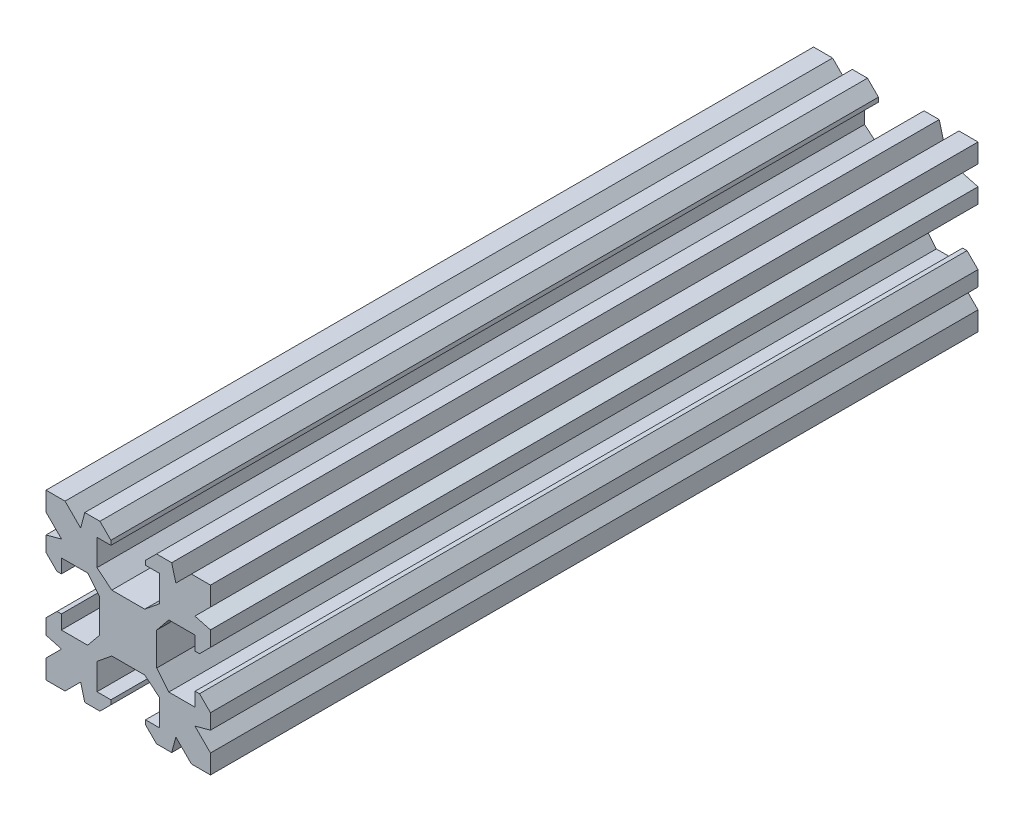
SolidWorks part; units mm, degrees
ref_plane "Спереди" through (0, 0, 0) normal (0, 0, 1) x (1, 0, 0)
ref_plane "Сверху" through (0, 0, 0) normal (0, 1, 0) x (1, 0, 0)
ref_plane "Справа" through (0, 0, 0) normal (1, 0, 0) x (0, 0, -1)
sketch "Эскиз1" plane through (0, 0, 0) normal (0, 0, 1) x (1, 0, 0)
  line L0 (1.58, 6.1) -> (2.85, 6.1)
  line L1 (-7.5, -7.5) -> (7.5, -7.5)
  line L2 (-7.5, -7.5) -> (-7.5, 7.5)
  line L3 (-7.5, 7.5) -> (7.5, 7.5)
  line L4 (7.5, -7.5) -> (7.5, 7.5)
  line L5 (-2.85, 6.1) -> (-1.58, 6.1)
  line L6 (-2.85, 6.1) -> (-2.85, 3.7)
  line L7 (-2.85, 3.7) -> (2.85, 3.7)
  line L8 (2.85, 6.1) -> (2.85, 3.7)
  line L9 (-2.85, 6.1) -> (2.85, 3.7) construction
  line L10 (-2.85, 3.7) -> (2.85, 6.1) construction
  line L11 (-1.58, 7.5) -> (1.58, 7.5)
  line L12 (-1.58, 7.5) -> (-1.58, 6.1)
  line L14 (1.58, 7.5) -> (1.58, 6.1)
  line L15 (-1.58, 7.5) -> (1.58, 6.1) construction
  line L16 (-1.58, 6.1) -> (1.58, 7.5) construction
  line L17 (6.1, -1.58) -> (6.1, -2.85)
  line L18 (6.1, 2.85) -> (6.1, 1.58)
  line L19 (6.1, 2.85) -> (3.7, 2.85)
  line L20 (3.7, 2.85) -> (3.7, -2.85)
  line L21 (6.1, -2.85) -> (3.7, -2.85)
  line L22 (7.5, 1.58) -> (7.5, -1.58)
  line L23 (7.5, 1.58) -> (6.1, 1.58)
  line L24 (7.5, -1.58) -> (6.1, -1.58)
  line L25 (6.1, 2.85) -> (3.7, -2.85) construction
  line L26 (3.7, 2.85) -> (6.1, -2.85) construction
  line L27 (7.5, 1.58) -> (6.1, -1.58) construction
  line L28 (6.1, 1.58) -> (7.5, -1.58) construction
  line L29 (-1.58, -6.1) -> (-2.85, -6.1)
  line L30 (2.85, -6.1) -> (1.58, -6.1)
  line L31 (2.85, -6.1) -> (2.85, -3.7)
  line L32 (2.85, -3.7) -> (-2.85, -3.7)
  line L33 (-2.85, -6.1) -> (-2.85, -3.7)
  line L34 (1.58, -7.5) -> (-1.58, -7.5)
  line L35 (1.58, -7.5) -> (1.58, -6.1)
  line L36 (-1.58, -7.5) -> (-1.58, -6.1)
  line L37 (2.85, -6.1) -> (-2.85, -3.7) construction
  line L38 (2.85, -3.7) -> (-2.85, -6.1) construction
  line L39 (1.58, -7.5) -> (-1.58, -6.1) construction
  line L40 (1.58, -6.1) -> (-1.58, -7.5) construction
  line L41 (-6.1, 1.58) -> (-6.1, 2.85)
  line L42 (-6.1, -2.85) -> (-6.1, -1.58)
  line L43 (-6.1, -2.85) -> (-3.7, -2.85)
  line L44 (-3.7, -2.85) -> (-3.7, 2.85)
  line L45 (-6.1, 2.85) -> (-3.7, 2.85)
  line L46 (-7.5, -1.58) -> (-7.5, 1.58)
  line L47 (-7.5, -1.58) -> (-6.1, -1.58)
  line L48 (-7.5, 1.58) -> (-6.1, 1.58)
  line L49 (-6.1, -2.85) -> (-3.7, 2.85) construction
  line L50 (-3.7, -2.85) -> (-6.1, 2.85) construction
  line L51 (-7.5, -1.58) -> (-6.1, 1.58) construction
  line L52 (-6.1, -1.58) -> (-7.5, 1.58) construction
  line L53 (-5.762, 7.5) -> (-4.342, 6.08)
  line L54 (-4.342, 6.08) -> (-3.962, 7.5)
  line L55 (-3.962, 7.5) -> (-5.762, 7.5)
  line L56 (-7.5, 7.5) -> (0, 0) construction
  line L57 (-6.08, 4.342) -> (-7.5, 3.962)
  line L58 (-7.5, 5.762) -> (-6.08, 4.342)
  line L59 (-7.5, 3.962) -> (-7.5, 5.762)
  line L60 (4.342, 6.08) -> (3.962, 7.5)
  line L61 (3.962, 7.5) -> (5.762, 7.5)
  line L62 (5.762, 7.5) -> (4.342, 6.08)
  line L63 (7.5, 3.962) -> (7.5, 5.762)
  line L64 (7.5, 5.762) -> (6.08, 4.342)
  line L65 (6.08, 4.342) -> (7.5, 3.962)
  line L66 (6.08, -4.342) -> (7.5, -3.962)
  line L67 (7.5, -3.962) -> (7.5, -5.762)
  line L68 (7.5, -5.762) -> (6.08, -4.342)
  line L69 (3.962, -7.5) -> (5.762, -7.5)
  line L70 (5.762, -7.5) -> (4.342, -6.08)
  line L71 (4.342, -6.08) -> (3.962, -7.5)
  line L72 (-4.342, -6.08) -> (-3.962, -7.5)
  line L73 (-3.962, -7.5) -> (-5.762, -7.5)
  line L74 (-5.762, -7.5) -> (-4.342, -6.08)
  line L75 (-7.5, -3.962) -> (-7.5, -5.762)
  line L76 (-7.5, -5.762) -> (-6.08, -4.342)
  line L77 (-6.08, -4.342) -> (-7.5, -3.962)
  point P0 (0, 0)
  point P5 (0, 4.9)
  point P12 (7.5, 0)
  point P13 (0, -7.5)
  point P14 (0, 6.8)
  point P19 (4.9, 0)
  point P26 (6.8, 0)
  point P31 (0, -4.9)
  point P36 (0, -6.8)
  point P41 (-4.9, 0)
  point P46 (-6.8, 0)
  point P51 (0, 0)
  point P77 (0, 0)
  dimension "D1" = 15
  dimension "D2" = 3.16
  dimension "D3" = 5.7
  dimension "D4" = 1.4
  dimension "D5" = 4
  dimension "D6" = 7.4
  dimension "D7" = 1.8
  dimension "D8" = 1.42
  dimension "D9" = 4
extrude "Бобышка-Вытянуть1" add sketch "Эскиз1" along normal blind 70 contours L77 L76 L2 L1 L74 L72 L36 L29 L33 L32 L31 L30 L35 L71 L70 L4 L68 L66 L24 L17 L21 L20 L19 L18 L23 L65 L64 L3 L62 L60 L14 L0 L8 L7 L6 L5 L12 L54 L53 L58 L57
sketch "Эскиз2" plane through (0, 0, 70) normal (0, 0, 1) x (1, 0, 0)
  line L0 (-3.7, 2.85) -> (-2.6, 1.5)
  line L1 (-2.6, 1.5) -> (-2.6, -1.5)
  line L2 (-2.6, -1.5) -> (-3.7, -2.85)
  line L3 (-3.7, -2.85) -> (-3.7, 2.85)
  line L4 (-7.5, -3.962) -> (-7.5, -1.58) construction
  line L5 (2.85, 3.7) -> (1.5, 2.6)
  line L6 (1.5, 2.6) -> (-1.5, 2.6)
  line L7 (-1.5, 2.6) -> (-2.85, 3.7)
  line L8 (-2.85, 3.7) -> (2.85, 3.7)
  line L9 (3.7, -2.85) -> (2.6, -1.5)
  line L10 (2.6, -1.5) -> (2.6, 1.5)
  line L11 (2.6, 1.5) -> (3.7, 2.85)
  line L12 (3.7, 2.85) -> (3.7, -2.85)
  line L13 (-2.85, -3.7) -> (-1.5, -2.6)
  line L14 (-1.5, -2.6) -> (1.5, -2.6)
  line L15 (1.5, -2.6) -> (2.85, -3.7)
  line L16 (2.85, -3.7) -> (-2.85, -3.7)
  point P6 (-2.6, 0)
  point P19 (0, 2.6)
  point P24 (2.6, 0)
  point P29 (0, -2.6)
  point P30 (0, 0)
  dimension "D1" = 3
  dimension "D2" = 4.9
  dimension "D3" = 4
extrude "Вырез-Вытянуть1" cut sketch "Эскиз2" against normal through all
chamfer "Фаска1" distance 1 angle 45 8 edges at (-7.5, 1.58, 35) (-7.5, -1.58, 35) (1.58, -7.5, 35) (-1.58, -7.5, 35) (7.5, -1.58, 35) (7.5, 1.58, 35) (1.58, 7.5, 35) (-1.58, 7.5, 35)
